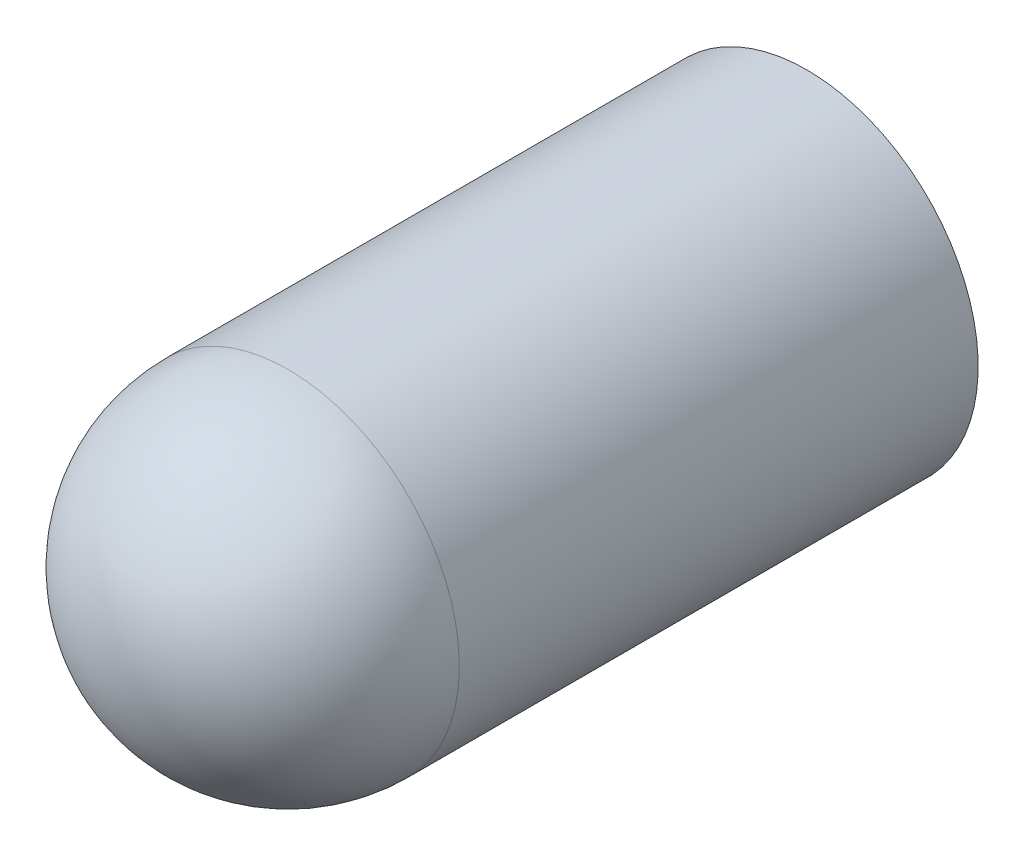
SolidWorks part; units mm, degrees
material "Custom Plastic"
ref_plane "X-Y Datum" through (0, 0, 0) normal (0, 0, 1) x (1, 0, 0)
ref_plane "X-Z Datum" through (0, 0, 0) normal (0, 1, 0) x (1, 0, 0)
ref_plane "Y-Z Datum" through (0, 0, 0) normal (1, 0, 0) x (0, 0, -1)
sketch "Sketch1" plane through (0, 0, 0) normal (0, 1, 0) x (1, 0, 0)
  line L8 (1.651, 0) -> (-1.651, 0) construction
  line L9 (1.651, 0) -> (1.651, -12.7)
  line L10 (-1.651, 0) -> (-1.651, -12.7) construction
  line L11 (1.651, 0) -> (4.191, 0)
  line L12 (4.191, 0) -> (4.191, -12.7)
  line L13 (-1.651, 0) -> (-4.191, 0) construction
  line L14 (-4.191, 0) -> (-4.191, -12.7) construction
  line L15 (0, 0) -> (0, -16.891) construction
  line L16 (0, -16.891) -> (0, -14.351)
  arc A0 (-1.651, -12.7) -> (1.651, -12.7) centre (0, -12.7) ccw construction
  arc A1 (-4.191, -12.7) -> (4.191, -12.7) centre (0, -12.7) ccw construction
  arc A2 (1.651, -12.7) -> (0, -14.351) centre (0, -12.7) cw
  arc A3 (4.191, -12.7) -> (0, -16.891) centre (0, -12.7) cw
  point P3 (0, 0)
  dimension "D2" = 12.7
  dimension "D1" = 3.302
  dimension "D3" = 2.54
revolve "Revolve2" add sketch "Sketch1" angle 360 about L15
